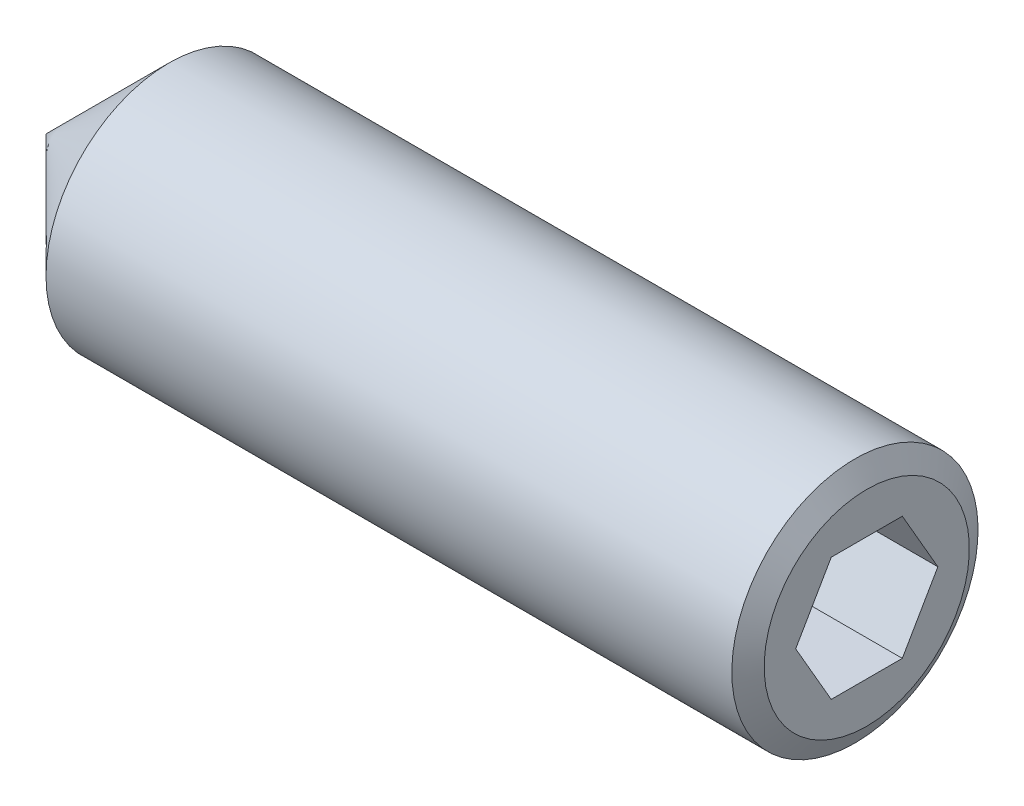
SolidWorks part; units mm, degrees
material "AISI 1020"
ref_plane "Front Plane" through (0, 0, 0) normal (0, 0, 1) x (1, 0, 0)
ref_plane "Top Plane" through (0, 0, 0) normal (0, 1, 0) x (1, 0, 0)
ref_plane "Right Plane" through (0, 0, 0) normal (1, 0, 0) x (0, 0, -1)
sketch "Sketch1" plane through (0, 0, 0) normal (0, 0, 1) x (1, 0, 0)
  line L0 (0, 0) -> (20, 0) construction
  line L1 (0, 0) -> (3, 3)
  line L2 (3, 3) -> (20, 3)
  line L4 (20, 3) -> (20, 0)
  line L5 (20, 0) -> (0, 0)
  line L6 (0, 0) -> (3, -3) construction
  dimension "Diam" = 6
  dimension "Kampas" = 90
  dimension "Ilgis" = 20
revolve "Revolve1" add sketch "Sketch1" angle 360 about L0
cosmetic thread "Cosmetic Thread1" parameters "Sr_diam"=5
sketch "Sketch2" plane through (20, 0, 0) normal (1, 0, 0) x (0, 0, -1)
  line L1 (1.7321, 0) -> (0.866, 1.5)
  line L2 (0.866, 1.5) -> (-0.866, 1.5)
  line L3 (-0.866, 1.5) -> (-1.7321, 0)
  line L4 (-1.7321, 0) -> (-0.866, -1.5)
  line L5 (-0.866, -1.5) -> (0.866, -1.5)
  line L6 (0.866, -1.5) -> (1.7321, 0)
  circle A0 centre (0, 0) radius 1.5 construction
  dimension "R_dydis" = 3
extrude "Cut-Extrude1" cut sketch "Sketch2" against normal blind 3.5
chamfer "Chamfer1" distance 0.5 angle 30 1 edges at (20, -3, 0)
